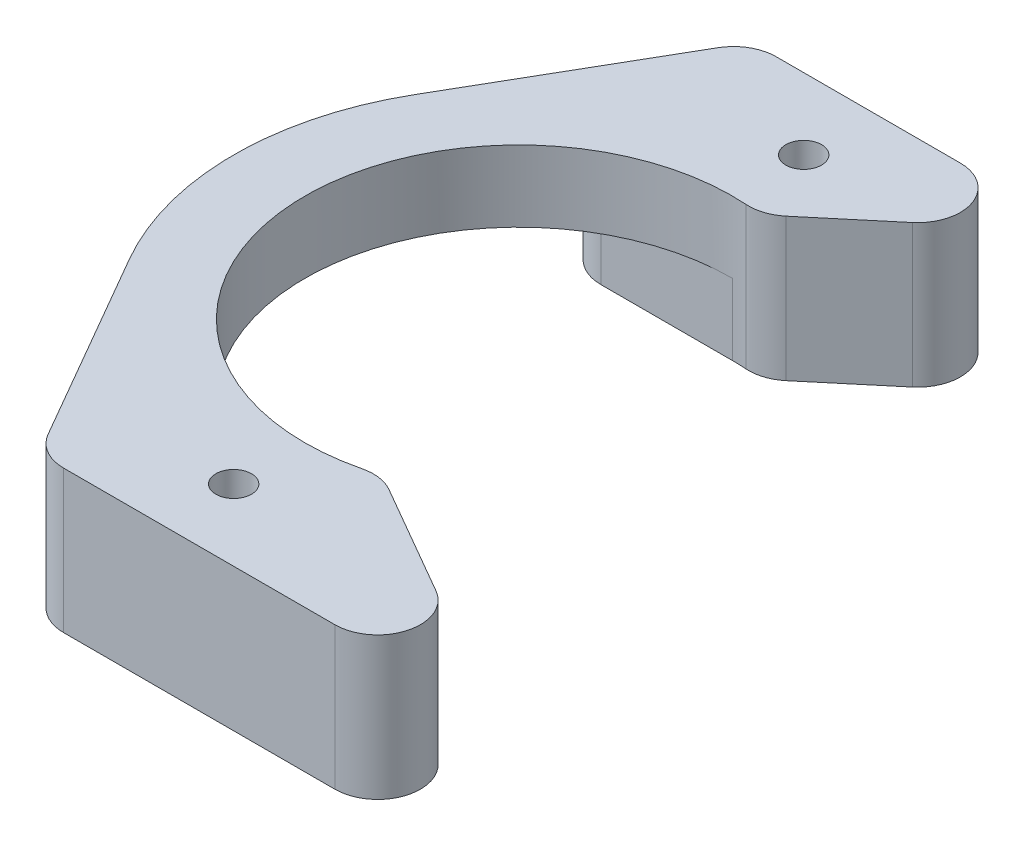
SolidWorks part; units mm, degrees
ref_plane "前视基准面" through (0, 0, 0) normal (0, 0, 1) x (1, 0, 0)
ref_plane "上视基准面" through (0, 0, 0) normal (0, 1, 0) x (1, 0, 0)
ref_plane "右视基准面" through (0, 0, 0) normal (1, 0, 0) x (0, 0, -1)
other "Configuration Table"
sketch "草图1" plane through (0, 0, 0) normal (0, 1, 0) x (1, 0, 0)
  line L0 (2.1368, 14.847) -> (6.8404, 18.7939)
  line L1 (4.6825, -14.2504) -> (10, -17.3205)
  line L2 (0, 0) -> (10, 0) construction
  line L3 (6.8404, 18.7939) -> (14.2366, 25)
  line L4 (14.2366, 25) -> (-8.6603, 25)
  line L5 (-8.6603, 25) -> (-17.3205, 10)
  line L6 (10, -17.3205) -> (23.3013, -25)
  line L7 (23.3013, -25) -> (-23.3013, -25)
  line L8 (23.3013, -25) -> (36.1146, 0) construction
  line L9 (0, 0) -> (0, -25) construction
  line L10 (36.1146, 0) -> (23.3013, 25) construction
  line L11 (23.3013, 25) -> (14.2366, 25) construction
  line L12 (23.3013, 25) -> (23.3013, -25) construction
  line L13 (10, 0) -> (36.1146, 0) construction
  line L14 (-17.3205, -10) -> (-8.6603, -25)
  circle A0 centre (0, 0) radius 10 construction
  arc A1 (2.1368, 14.847) -> (4.6825, -14.2504) centre (0, 0) ccw
  arc A2 (6.8404, 18.7939) -> (10, -17.3205) centre (0, 0) ccw
  dimension "D1" = 20
  dimension "D4" = 30
  dimension "D5" = 40
  dimension "D2" = 30
  dimension "D3" = 40
  dimension "D6" = 120
  dimension "D7" = 25
extrude "凸台-拉伸1" add sketch "草图1" along normal blind 10 contours A2 L3 L4 L5 | L0 A2 L1 A1 | A2 L14 L7 L6
sketch "草图2" plane through (0, 0, 0) normal (0, -1, 0) x (1, 0, 0)
  line L0 (0, 20) -> (0, -20) construction
  point P0 (0, 20)
  point P1 (0, -20)
  point P3 (0, 0)
  dimension "D1" = 40
hole_wizard "M3 螺纹孔1" positions "草图2" profile "草图3" tap size "M3" standard "GB" end condition through all
sketch "草图3" plane through (0, 0, 20) normal (1, 0, 0) x (0, 0, -1)
  line L0 (0, 0) -> (0, 10)
  line L1 (0, 10) -> (1.25, 10)
  line L2 (1.25, 10) -> (1.25, 0)
  line L5 (1.25, 0) -> (0, 0)
  line L11 (0, -6.35) -> (0, 107.95) construction
  dimension "通孔螺纹孔钻头直径" = 2.5
  dimension "通孔螺纹孔钻头深度" = 10
cosmetic thread "孔螺纹线1" parameters "D2"=3
cosmetic thread "孔螺纹线2" parameters "D2"=3
sketch "草图4" plane through (0, 0, 0) normal (0, -1, 0) x (1, 0, 0)
  line L0 (0, 15) -> (-14.4338, 15)
  line L1 (-17.3205, 10) -> (-8.6603, 25) construction
  line L2 (-14.4338, 15) -> (-17.3205, 10)
  line L3 (0, -15) -> (-14.4338, -15)
  line L4 (-8.6603, -25) -> (-17.3205, -10) construction
  line L5 (-14.4338, -15) -> (-17.3205, -10)
  line L6 (0, 15) -> (0, -15)
  arc A0 (4.6825, 14.2504) -> (2.1368, -14.847) centre (0, 0) ccw construction
  arc A1 (-17.3205, 10) -> (-17.3205, -10) centre (0, 0) ccw construction
  arc A2 (-17.3205, 10) -> (-17.3205, -10) centre (0, 0) ccw
extrude "切除-拉伸1" cut sketch "草图4" against normal blind 5
fillet "圆角1" radius 3 8 edges at (-8.6603, 5, 25) (-8.6603, 5, -25) (14.2366, 5, -25) (23.3013, 5, 25) (4.6825, 5, 14.2504) (2.1368, 5, -14.847) (-14.4338, 2.5, -15) (-14.4338, 2.5, 15)
